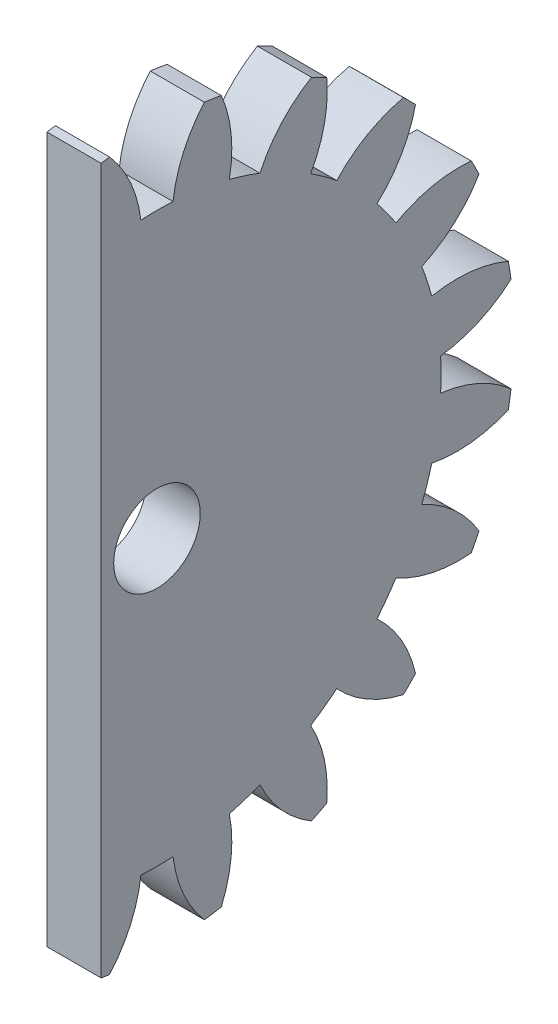
SolidWorks part; units mm, degrees
ref_plane "Plane1" through (0, 0, 0) normal (0, 0, 1) x (1, 0, 0)
ref_plane "Plane2" through (0, 0, 0) normal (0, 1, 0) x (1, 0, 0)
ref_plane "Plane3" through (0, 0, 0) normal (1, 0, 0) x (0, 0, -1)
other "Configuration Table"
sketch "HoldingSke" plane through (0, 0, 0) normal (0, 1, 0) x (1, 0, 0)
  line L0 (0, 0) -> (0.6265, -0.228)
  line L1 (-15, 0) -> (100, 0) construction
  line L2 (0, 0) -> (-2.1039, 2.3779)
  line L3 (0, 0) -> (-11.863, 4.5341)
  line L4 (0, 0) -> (8.1152, 2.9537)
  line L5 (0, 0) -> (-46.8476, -17.4728)
  line L6 (0, 0) -> (-2.0724, -1.3983)
  line L7 (-2.1039, 2.3779) -> (8.6586, 51.2059)
  line L8 (-76.2, 54.61) -> (-75.5, 54.61)
  line L9 (-71.009, 38.7566) -> (-53.1078, 45.2721)
  line L10 (-76.2, 71.12) -> (104.1128, 71.12)
  line L11 (0, 0) -> (-2.5, 0)
  line L12 (-76.2, 101.6) -> (-76.147, 101.6)
  line L13 (24.9733, 27.94) -> (52.9518, 28.4284)
  line L14 (24.9733, 27.94) -> (24.9743, 27.94)
  line L15 (24.9733, 27.94) -> (100.4006, 29.5858)
  line L16 (-63.627, -1.5) -> (-12.827, -1.5)
  circle A0 centre (0, 0) radius 2
  circle A1 centre (0, 0) radius 13.124
  circle A2 centre (0, 0) radius 37.5
  circle A3 centre (0, 0) radius 2
  dimension "MHD" = 26.248
  dimension "Hub_dia" = 75
  dimension "Bore" = 4
  dimension "MBD" = 4
  dimension "Num_teeth" = 20
  dimension "Pitch" = 0.6667
  dimension "Overall_len" = 50
  dimension "Show_teeth" = 20
  dimension "Thickness" = 2.5
  dimension "OAL" = 50.0001
  dimension "T_dim" = 0.7
  dimension "Ap" = 20
  dimension "H" = 19.05
  dimension "Pitch_radius" = 180.3128
  dimension "Width" = 2.5
  dimension "Backlash" = 0.053
  dimension "Addendum_fac" = 1
  dimension "Dedendum_fac" = 1.25
  dimension "Clearance_fac" = 0.25
  dimension "Dedendum_add" = 0.001
  dimension "Module" = 1.5
sketch "BasProSke" plane through (0, 0, 0) normal (0, 1, 0) x (1, 0, 0)
  line L0 (-10, 0) -> (60, 0) construction
  line L1 (0, 0) -> (0, 16.5)
  line L2 (0, 0) -> (2.5, 0)
  line L3 (2.5, 0) -> (2.5, 16.5)
  line L4 (2.5, 16.5) -> (0, 16.5)
  dimension "Thickness" = 2.5
  dimension "Diameter" = 33
revolve "Base-Revolve" add sketch "BasProSke" angle 360 about L0
sketch "TooCutSke" plane through (0, 0, 0) normal (1, 0, 0) x (0, 0, -1)
  line L1 (0, 0) -> (0, 107) construction
  line L2 (0, 0) -> (-1.2696, 14.9462) construction
  line L3 (0, 0) -> (-4.6808, 29.5532) construction
  line L4 (-1.2696, 14.9462) -> (-2.3404, 14.7766) construction
  arc A0 (0.7438, 13.1029) -> (-0.7438, 13.1029) centre (0, 0) ccw
  arc A1 (2.21, 16.377) -> (-2.21, 16.377) centre (0, 0) ccw
  circle A2 centre (0, 0) radius 15 construction
  circle A3 centre (0, 0) radius 14.0954 construction
  arc A4 (-0.7438, 13.1029) -> (-2.21, 16.377) centre (-6.7025, 12.3999) ccw
  arc A5 (2.21, 16.377) -> (0.7438, 13.1029) centre (6.7025, 12.3999) ccw
  dimension "Root_dia" = 26.248
  dimension "Overcut_dia" = 33.0508
  dimension "Pitch_dia" = 30
  dimension "Base_dia" = 28.1908
  dimension "Flank_rad" = 6
  dimension "Half_ang" = 9
  dimension "Half_CT" = 1.0841
extrude "ToothCut" cut sketch "TooCutSke" along normal through all
fillet "Breaks" [suppressed] radius 0.03
fillet "RootFillets" [suppressed] radius 0.376
pattern_circular "TeethCuts" count 20 every 18 about axis through (-10, 0, 0) along (1, 0, 0) of "ToothCut", "RootFillets", "Breaks"
sketch "HubNeaOneSke" plane through (0, 0, 0) normal (-1, 0, 0) x (0, 0, 1)
  circle A0 centre (0, 0) radius 13.124
  dimension "Diameter" = 26.248
extrude "HubNearOne" [suppressed] add sketch "HubNeaOneSke" along normal blind 47.5001
sketch "HubNeaBotSke" plane through (0, 0, 0) normal (-1, 0, 0) x (0, 0, 1)
  circle A0 centre (0, 0) radius 13.124
  dimension "Diameter" = 26.248
extrude "HubNearBoth" [suppressed] add sketch "HubNeaBotSke" along normal blind 23.75
ref_plane "FarPln" through (2.5, 0, 0) normal (1, 0, 0) x (0, 0, -1)
sketch "HubFarSke" plane through (2.5, 0, 0) normal (1, 0, 0) x (0, 0, -1)
  circle A0 centre (0, 0) radius 13.124
  dimension "Diameter" = 26.248
extrude "HubFar" [suppressed] add sketch "HubFarSke" along normal blind 23.75
sketch "BorSke" plane through (0, 0, 0) normal (1, 0, 0) x (0, 0, -1)
  circle A0 centre (0, 0) radius 2
  dimension "Diameter" = 4
extrude "Bore" cut sketch "BorSke" along normal mid plane 100.0001
sketch "KeySke" plane through (0, 0, 0) normal (1, 0, 0) x (0, 0, -1)
  line L0 (-0.8, 0) -> (-0.8, 2.7)
  line L1 (-0.8, 2.7) -> (0.8, 2.7)
  line L2 (0.8, 2.7) -> (0.8, 0)
  line L3 (0, 0) -> (0, 34) construction
  line L4 (-0.8, 0) -> (0.8, 0)
  dimension "Offset" = 2.7
  dimension "Width" = 1.6
extrude "Keyway" [suppressed] cut sketch "KeySke" along normal mid plane 100.0001
pattern_circular "Keyway2" [suppressed] count 2 every 90 about axis through (-10, 0, 0) along (1, 0, 0)
sketch "Sketch1" plane through (2.5, 0, 0) normal (1, 0, 0) x (0, 0, -1)
  line L0 (-2.5812, -16.2969) -> (-2.5812, 29.9436)
  line L1 (-2.5812, 29.9436) -> (-16.6111, 29.9436)
  line L2 (-16.6111, 29.9436) -> (-16.6111, -16.2969)
  line L3 (-16.6111, -16.2969) -> (-2.5812, -16.2969)
  arc A0 (-2.9711, -16.2303) -> (-2.1898, -16.354) centre (0, 0) ccw construction
  point P3 (-2.5812, -16.2969)
extrude "Cut-Extrude1" cut sketch "Sketch1" against normal through all
equation "' \"Module@HoldingSke\" = 6.35"
equation "' \"Num_teeth@HoldingSke\" = 12"
equation "' \"Ap@HoldingSke\" =  20"
equation "' \"Ap@HoldingSke\" = 20"
equation "' \"Width@HoldingSke\" = 0.5 * 25.4"
equation "' \"Hub_dia@HoldingSke\"= 1 * 25.4"
equation "' \"Hub_dia@HoldingSke\" = 1 * 25.4"
equation "' \"Overall_len@HoldingSke\" = 1.0 * 25.4"
equation "' \"Bore@HoldingSke\" = 0.75 * 25.4"
equation "' \"T_dim@HoldingSke\" = 0.1 * 25.4"
equation "' \"Width@KeySke\" = 0.25 * 25.4"
equation "' \"Show_teeth@HoldingSke\" = 13"
equation "' \"Backlash@HoldingSke\" = 0.009 * 25.4"
equation "' \"Addendum_fac@HoldingSke\" = 1.0"
equation "' \"Dedendum_fac@HoldingSke\" = 1.25"
equation "' \"Dedendum_add@HoldingSke\" = 0.00005 * 25.4"
equation "' \"Clearance_fac@HoldingSke\" = 0.25"
equation "\"Pitch@HoldingSke\" = 1 / \"Module@HoldingSke\""
equation "\"Overcut_dia@TooCutSke\" = (\"Num_teeth@HoldingSke\" + 2 * \"Addendum_fac@HoldingSke\") / \"Pitch@HoldingSke\" + 0.002 * 25.4"
equation "\"Pitch_dia@TooCutSke\" = \"Num_teeth@HoldingSke\" / \"Pitch@HoldingSke\""
equation "\"Base_dia@TooCutSke\" = \"Num_teeth@HoldingSke\" / \"Pitch@HoldingSke\" * cos((\"Ap@HoldingSke\"  * 3.14159265 / 180))"
equation "\"Root_dia@TooCutSke\" = (\"Num_teeth@HoldingSke\" + 2) / \"Pitch@HoldingSke\" - 2 * (\"Addendum_fac@HoldingSke\" + \"Dedendum_fac@HoldingSke\") / \"Pitch@HoldingSke\" - \"Dedendum_add@HoldingSke\" * 2"
equation "\"Half_ang@TooCutSke\" = 180 / \"Num_teeth@HoldingSke\""
equation "\"Half_CT@TooCutSke\" = \"Num_teeth@HoldingSke\" / \"Pitch@HoldingSke\" * sin((3.14159265 / 2 / \"Num_teeth@HoldingSke\")) / 2 - 7 * \"Backlash@HoldingSke\" / 4"
equation "\"Flank_rad@TooCutSke\" = \"Num_teeth@HoldingSke\" / \"Pitch@HoldingSke\" / 5"
equation "\"Radius@RootFillets\" = \"Clearance_fac@HoldingSke\" / \"Pitch@HoldingSke\" + \"Dedendum_add@HoldingSke\""
equation "\"Break_rad@Breaks\" = 0.02 / \"Pitch@HoldingSke\""
equation "\"Thickness@HoldingSke\" = \"Width@HoldingSke\""
equation "\"OAL@HoldingSke\" = \"Thickness@HoldingSke\""
equation "\"MHD@HoldingSke\" = (\"Num_teeth@HoldingSke\" + 2) / \"Pitch@HoldingSke\" - 2 * (\"Addendum_fac@HoldingSke\" + \"Dedendum_fac@HoldingSke\")  / \"Pitch@HoldingSke\" - \"Dedendum_add@HoldingSke\" * 2"
equation "\"MBD@HoldingSke\" = (\"Num_teeth@HoldingSke\" + 2) / \"Pitch@HoldingSke\" - 2 * (\"Addendum_fac@HoldingSke\" + \"Dedendum_fac@HoldingSke\")  / \"Pitch@HoldingSke\" - \"Dedendum_add@HoldingSke\" * 2 - 0.002 * 25.4"
equation "\"MHD@HoldingSke\" = ((sgn( \"MHD@HoldingSke\" - \"Hub_dia@HoldingSke\" )-1)*( \"MHD@HoldingSke\" - \"Hub_dia@HoldingSke\" ))/-2+ \"Hub_dia@HoldingSke\""
equation "\"MBD@HoldingSke\" = ((sgn( \"MBD@HoldingSke\" - \"Bore@HoldingSke\" )-1)*( \"MBD@HoldingSke\" - \"Bore@HoldingSke\" ))/-2+ \"Bore@HoldingSke\""
equation "\"OAL@HoldingSke\" = ((sgn( \"OAL@HoldingSke\" - \"Overall_len@HoldingSke\" )+1)*( \"OAL@HoldingSke\" - \"Overall_len@HoldingSke\" ))/2 + \"Overall_len@HoldingSke\" + 0.000002 * 25.4"
equation "\"Num_teeth@TeethCuts\" = int( \"Show_teeth@HoldingSke\" ) + 1"
equation "\"Num_teeth@TeethCuts\" = ((sgn( \"Num_teeth@TeethCuts\" - \"Num_teeth@HoldingSke\" )-1)*( \"Num_teeth@TeethCuts\" - \"Num_teeth@HoldingSke\" ))/-2+ \"Num_teeth@HoldingSke\""
equation "\"Num_teeth@TeethCuts\" = ((sgn( \"Num_teeth@TeethCuts\" - 2.0)+1)*( \"Num_teeth@TeethCuts\" - 2.0))/2 +2.0"
equation "\"Angle@TeethCuts\" = 360.0 / \"Num_teeth@HoldingSke\""
equation "\"Diameter@BasProSke\" = (\"Num_teeth@HoldingSke\" + 2 * \"Addendum_fac@HoldingSke\") / \"Pitch@HoldingSke\""
equation "\"Thickness@BasProSke\"  = \"Thickness@HoldingSke\""
equation "' \"Fillet_rad@BasProSke\" =  \"Thickness@HoldingSke\" * 0.05"
equation "' \"Fillet_rad@BasProSke\" = \"Thickness@HoldingSke\" * 0.05"
equation "\"MHD@HoldingSke\" = ((sgn( \"MHD@HoldingSke\" - \"Root_dia@TooCutSke\" )-1)*( \"MHD@HoldingSke\" - \"Root_dia@TooCutSke\" ))/-2+ \"Root_dia@TooCutSke\""
equation "\"Diameter@HubNeaOneSke\" = \"MHD@HoldingSke\""
equation "\"Length@HubNearOne\" = \"OAL@HoldingSke\" - \"Thickness@BasProSke\""
equation "\"Diameter@HubNeaBotSke\" = \"MHD@HoldingSke\""
equation "\"Length@HubNearBoth\" = ( \"OAL@HoldingSke\" - \"Thickness@BasProSke\" ) / 2.0"
equation "\"Thickness@FarPln\" = \"Thickness@BasProSke\""
equation "\"Diameter@HubFarSke\" = \"MHD@HoldingSke\""
equation "\"Length@HubFar\" = ( \"OAL@HoldingSke\" - \"Thickness@BasProSke\" ) / 2.0"
equation "\"Diameter@BorSke\" = \"MBD@HoldingSke\""
equation "\"D1@Bore\" = \"OAL@HoldingSke\" * 2.0"
equation "\"D1@Keyway\" = \"OAL@HoldingSke\" * 2.0"
equation "\"Offset@KeySke\" = \"T_dim@HoldingSke\" + \"MBD@HoldingSke\" / 2.0"
